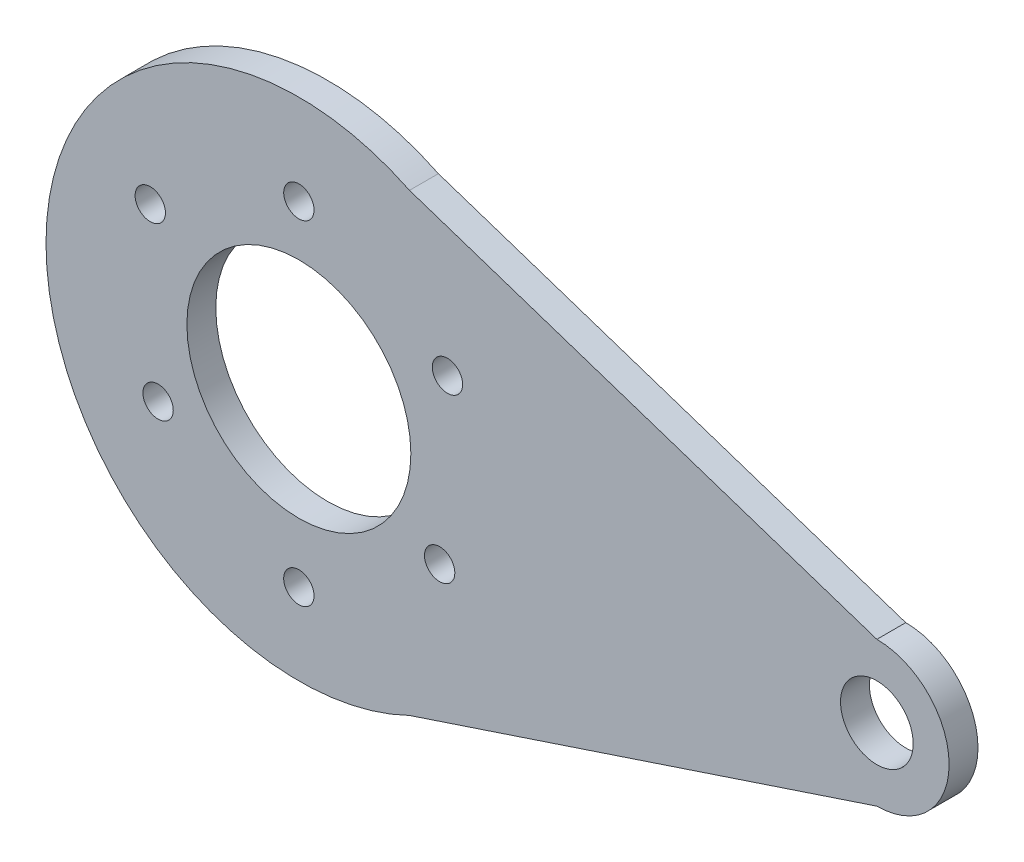
SolidWorks part; units mm, degrees
ref_plane "前视基准面" through (0, 0, 0) normal (0, 0, 1) x (1, 0, 0)
ref_plane "上视基准面" through (0, 0, 0) normal (0, 1, 0) x (1, 0, 0)
ref_plane "右视基准面" through (0, 0, 0) normal (1, 0, 0) x (0, 0, -1)
sketch "草图2" plane through (0, 0, 0) normal (0, 0, 1) x (1, 0, 0)
  line L0 (2.5741, -5.5276) -> (41.8465, -28.2015) construction
  line L1 (2.5741, -5.5276) -> (82.5741, -5.5276) construction
  line L5 (82.5741, 4.4724) -> (17.8866, 25.9451)
  line L6 (17.8866, -37.0002) -> (82.5741, -15.5276)
  circle A0 centre (2.5741, -5.5276) radius 23.75 construction
  circle A1 centre (2.5741, -5.5276) radius 22.5 construction
  circle A2 centre (2.5741, -29.2776) radius 2.1
  circle A3 centre (22.0596, -16.7776) radius 2.1
  circle A4 centre (2.5741, -5.5276) radius 35 construction
  arc A5 (17.8866, 25.9451) -> (17.8866, -37.0002) centre (2.5741, -5.5276) ccw
  circle A6 centre (2.5741, -5.5276) radius 15.5
  circle A11 centre (82.5741, -5.5276) radius 5.03
  circle A12 centre (82.5741, -5.5276) radius 10 construction
  arc A13 (82.5741, 4.4724) -> (82.5741, -15.5276) centre (82.5741, -5.5276) cw
  circle A14 centre (-17.994, 6.3474) radius 2.1
  circle A15 centre (23.1422, 6.3474) radius 2.1
  circle A16 centre (2.5741, 16.9724) radius 2.1
  circle A17 centre (-16.9115, -16.7776) radius 2.1
  dimension "D1" = 45
  dimension "D2" = 4.2
  dimension "D4" = 70
  dimension "D5" = 10.06
  dimension "D6" = 47.5
  dimension "D7" = 3
  dimension "D8" = 3
extrude "凸台-拉伸1" add sketch "草图2" along normal blind 4
